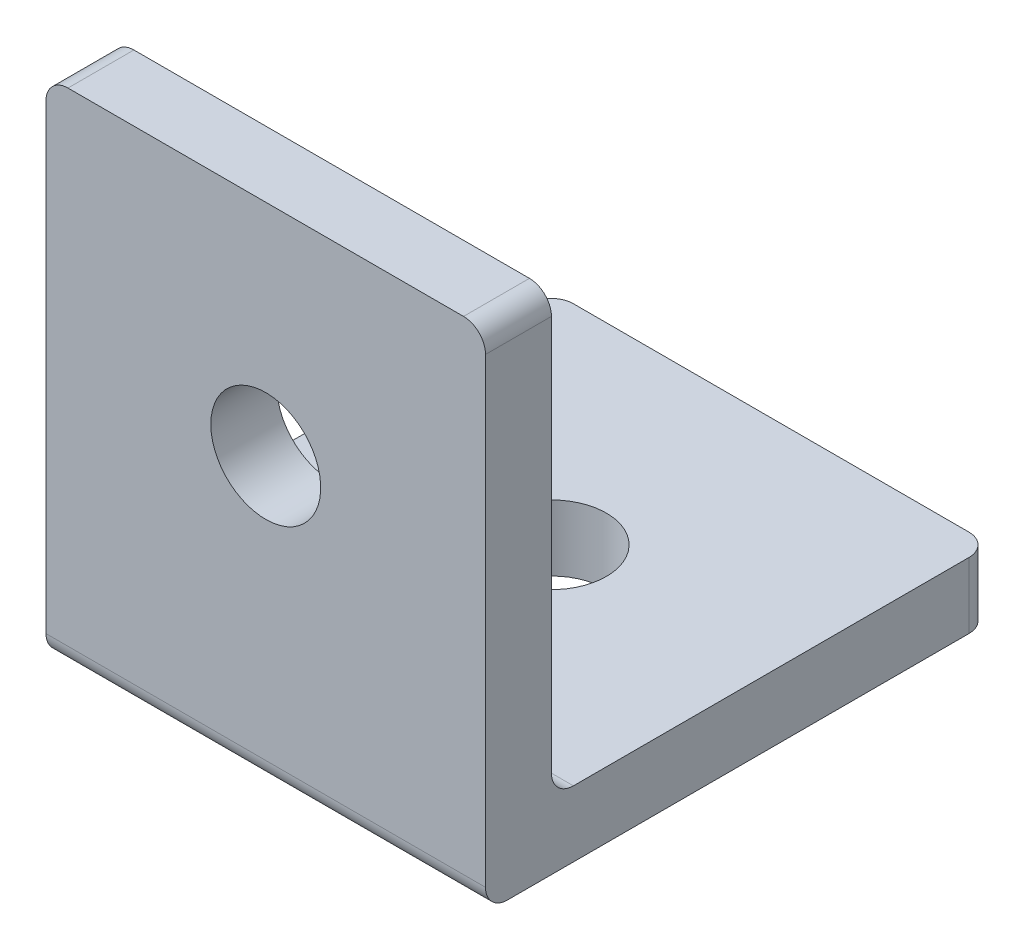
SolidWorks part; units mm, degrees
material "A5083"
ref_plane "Front" through (0, 0, 0) normal (0, 0, 1) x (1, 0, 0)
ref_plane "Top" through (0, 0, 0) normal (0, 1, 0) x (1, 0, 0)
ref_plane "Right" through (0, 0, 0) normal (1, 0, 0) x (0, 0, -1)
sketch "Sketch2" plane through (0, 0, 0) normal (1, 0, 0) x (0, 0, -1)
  line L1 (1, 0) -> (23, 0)
  line L3 (4, 3) -> (23, 3)
  line L4 (23, 0) -> (23, 3)
  line L6 (0, 1) -> (0, 23)
  line L7 (0, 23) -> (3, 23)
  line L8 (3, 4) -> (3, 23)
  arc A0 (1, 0) -> (0, 1) centre (1, 1) cw
  arc A1 (3, 4) -> (4, 3) centre (4, 4) ccw
  point P7 (0, 12.8407)
  point P9 (-10.2612, 0)
  point P11 (0, 0)
  dimension "D5" = 1
  dimension "D1" = 23
  dimension "D2" = 23
  dimension "D3" = 3
  dimension "D4" = 3
extrude "Boss-Extrude1" add sketch "Sketch2" against normal blind 20
fillet "Fillet1" radius 1 4 edges at (-20, 1.5, -23) (0, 1.5, -23) (-20, 23, -1.5) (0, 23, -1.5)
sketch "Sketch3" plane through (0, 0, -3) normal (0, 0, -1) x (-1, 0, 0)
  line L0 (19, 23) -> (1, 23) construction
  line L1 (0, 4) -> (0, 22) construction
  circle A0 centre (10, 13) radius 2.5
  dimension "D1" = 5
  dimension "D2" = 10
  dimension "D3" = 10
extrude "Cut-Extrude1" cut sketch "Sketch3" against normal through all
sketch "Sketch4" plane through (0, 3, 0) normal (0, 1, 0) x (1, 0, 0)
  line L0 (-19, 23) -> (-1, 23) construction
  line L1 (-20, 22) -> (-20, 4) construction
  circle A0 centre (-10, 13) radius 2.5
  dimension "D1" = 5
  dimension "D2" = 10
  dimension "D3" = 10
extrude "Cut-Extrude2" cut sketch "Sketch4" against normal through all
